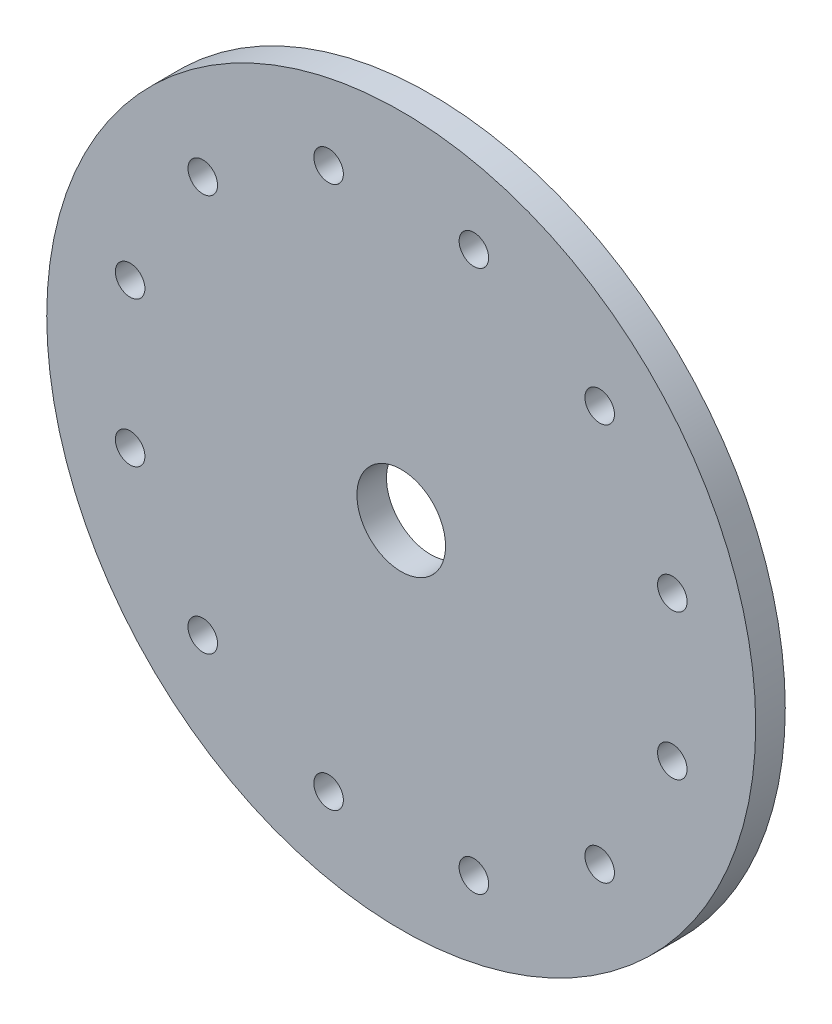
SolidWorks part; units mm, degrees
ref_plane "Front Plane" through (0, 0, 0) normal (0, 0, 1) x (1, 0, 0)
ref_plane "Top Plane" through (0, 0, 0) normal (0, 1, 0) x (1, 0, 0)
ref_plane "Right Plane" through (0, 0, 0) normal (1, 0, 0) x (0, 0, -1)
sketch "Sketch1" plane through (0, 0, 0) normal (0, 0, 1) x (1, 0, 0)
  circle A0 centre (0, 0) radius 19.05
  circle A1 centre (0, 0) radius 152.4
extrude "Boss-Extrude1" add sketch "Sketch1" along normal blind 12.7
sketch "Sketch2" plane through (0, 0, 0) normal (0, 0, 1) x (1, 0, 0)
  circle A2 centre (85.3124, 85.3124) radius 6.35
sketch "Sketch3" plane through (0, 0, 0) normal (0, 0, 1) x (1, 0, 0)
  circle A2 centre (0, 0) radius 120.65
  circle A3 centre (0, 0) radius 120.65
  dimension "D1" = 31.75
extrude "Cut-Extrude2" cut sketch "Sketch2" against normal through all and the other way through all contours A2
pattern_curve "CrvPattern1" of "Cut-Extrude2" parameters "D1"=12, "D3"=50, "D2"=1, "D4"=50
